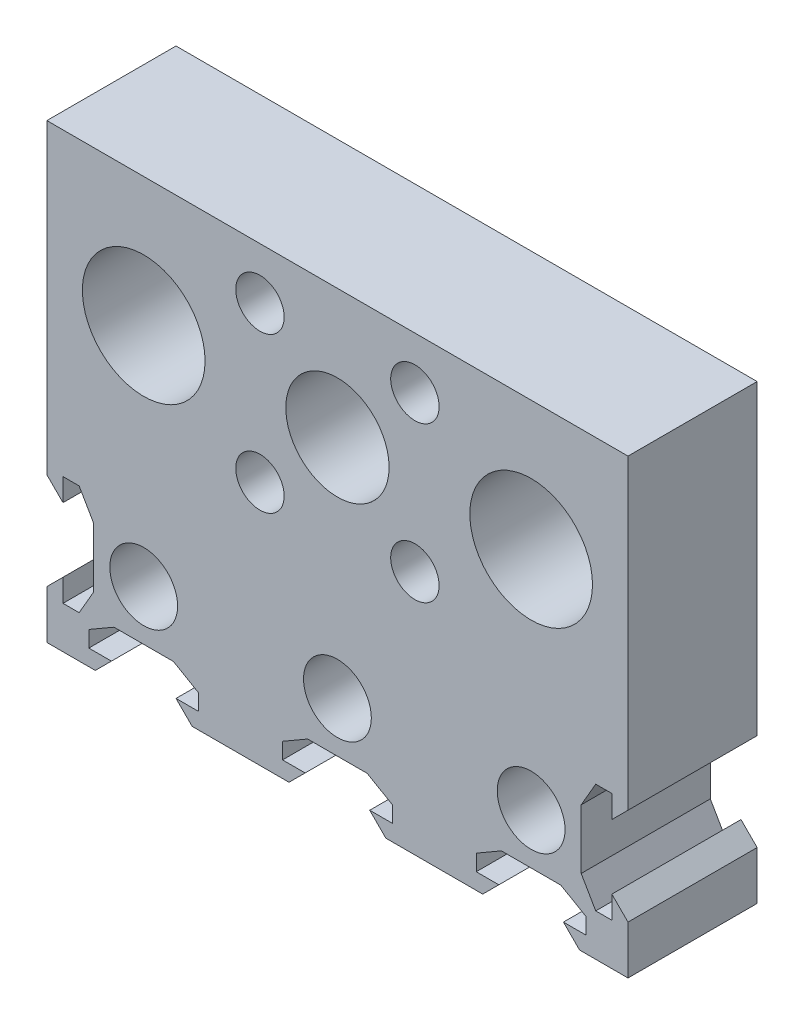
SolidWorks part; units mm, degrees
ref_plane "Alzado" through (0, 0, 0) normal (0, 0, 1) x (1, 0, 0)
ref_plane "Planta" through (0, 0, 0) normal (0, 1, 0) x (1, 0, 0)
ref_plane "Vista lateral" through (0, 0, 0) normal (1, 0, 0) x (0, 0, -1)
sketch "Sketch1" plane through (0, 0, 0) normal (0, 0, 1) x (1, 0, 0)
  line L0 (0, 0) -> (0, 50000) construction
  line L1 (45, 70) -> (-45, 70)
  line L2 (45, 70) -> (45, 22.5)
  line L3 (-45, 0) -> (-37.5, 0)
  line L4 (-45, 70) -> (-45, 22.5)
  line L5 (45, 70) -> (-45, 0) construction
  line L6 (45, 0) -> (-45, 70) construction
  line L7 (-45, 0) -> (-45, 7.5)
  line L8 (-22.5, 0) -> (-7.5, 0)
  line L9 (7.5, 0) -> (22.5, 0)
  line L10 (37.5, 0) -> (45, 0)
  line L17 (45, 7.5) -> (45, 0)
  circle A0 centre (0, 15) radius 5.25
  circle A1 centre (-30, 15) radius 5.25
  circle A2 centre (30, 15) radius 5.25
  circle A3 centre (0, 50) radius 8
  circle A4 centre (30, 50) radius 9.5
  circle A5 centre (12, 62) radius 3.75
  circle A6 centre (12, 38) radius 3.75
  circle A7 centre (-12, 38) radius 3.75
  circle A8 centre (-12, 62) radius 3.75
  circle A9 centre (-30, 50) radius 9.5
  circle A11 centre (-30, 50) radius 9.5 construction
  point P0 (0, 35)
  line B0 (42.5, 20) -> (42.5, 23.5)
  line B1 (42.5, 23.5) -> (40, 23.5)
  line B2 (40, 23.5) -> (37.75, 19.6029)
  line B3 (37.75, 19.6029) -> (37.75, 10.3971)
  line B4 (37.75, 15) -> (45, 15) construction
  line B5 (42.5, 20) -> (45, 22.5)
  line B6 (42.5, 10) -> (45, 7.5)
  line B7 (40, 6.5) -> (37.75, 10.3971)
  line B8 (42.5, 6.5) -> (40, 6.5)
  line B9 (42.5, 10) -> (42.5, 6.5)
  line B10 (35, 2.5) -> (38.5, 2.5)
  line B11 (38.5, 2.5) -> (38.5, 5)
  line B12 (38.5, 5) -> (34.6029, 7.25)
  line B13 (34.6029, 7.25) -> (25.3971, 7.25)
  line B14 (30, 7.25) -> (30, 0) construction
  line B15 (35, 2.5) -> (37.5, 0)
  line B16 (25, 2.5) -> (22.5, 0)
  line B17 (21.5, 5) -> (25.3971, 7.25)
  line B18 (21.5, 2.5) -> (21.5, 5)
  line B19 (25, 2.5) -> (21.5, 2.5)
  line B20 (-35, 2.5) -> (-38.5, 2.5)
  line B21 (-38.5, 2.5) -> (-38.5, 5)
  line B22 (-38.5, 5) -> (-34.6029, 7.25)
  line B23 (-34.6029, 7.25) -> (-25.3971, 7.25)
  line B24 (-30, 7.25) -> (-30, 0) construction
  line B25 (-35, 2.5) -> (-37.5, 0)
  line B26 (-25, 2.5) -> (-22.5, 0)
  line B27 (-21.5, 5) -> (-25.3971, 7.25)
  line B28 (-21.5, 2.5) -> (-21.5, 5)
  line B29 (-25, 2.5) -> (-21.5, 2.5)
  line B30 (5, 2.5) -> (8.5, 2.5)
  line B31 (8.5, 2.5) -> (8.5, 5)
  line B32 (8.5, 5) -> (4.6029, 7.25)
  line B33 (4.6029, 7.25) -> (-4.6029, 7.25)
  line B34 (0, 7.25) -> (0, 0) construction
  line B35 (5, 2.5) -> (7.5, 0)
  line B36 (-5, 2.5) -> (-7.5, 0)
  line B37 (-8.5, 5) -> (-4.6029, 7.25)
  line B38 (-8.5, 2.5) -> (-8.5, 5)
  line B39 (-5, 2.5) -> (-8.5, 2.5)
  line B40 (-42.5, 20) -> (-42.5, 23.5)
  line B41 (-42.5, 23.5) -> (-40, 23.5)
  line B42 (-40, 23.5) -> (-37.75, 19.6029)
  line B43 (-37.75, 19.6029) -> (-37.75, 10.3971)
  line B44 (-37.75, 15) -> (-45, 15) construction
  line B45 (-42.5, 20) -> (-45, 22.5)
  line B46 (-42.5, 10) -> (-45, 7.5)
  line B47 (-40, 6.5) -> (-37.75, 10.3971)
  line B48 (-42.5, 6.5) -> (-40, 6.5)
  line B49 (-42.5, 10) -> (-42.5, 6.5)
sketch_block_instance "Block1-1"
sketch_block "Block1" parameters "D1"=45, "D2"=60, "D3"=10, "D4"=3.5, "D5"=2.5, "D6"=4.5
sketch_block_instance "Block1-2"
sketch_block_instance "Block1-3"
sketch_block_instance "Block1-4"
sketch_block_instance "Block1-5" parameters "D3"=10.5, "D4"=15, "D5"=12, "D6"=9.9562, "D7"=20.6825, "D1"=43.6236, "D2"=101.498, "D8"=0.8961, "D9"=3.4992, "D10"=2.4142, "D11"=4.7537, "D12"=9.2058
extrude "Boss-Extrude1" add sketch "Sketch1" along normal mid plane 20 contours B49 B46 L7 L3 B25 B20 B21 B22 B23 B27 B28 B29 B26 L8 B36 B39 B38 B37 B33 B32 B31 B30 B35 L9 B16 B19 B18 B17 B13 B12 B11 B10 B15 L10 L17 B6 B9 B8 B7 B3 B2 B1 B0 B5 L2 L1 L4 B45 B40 B41 B42
